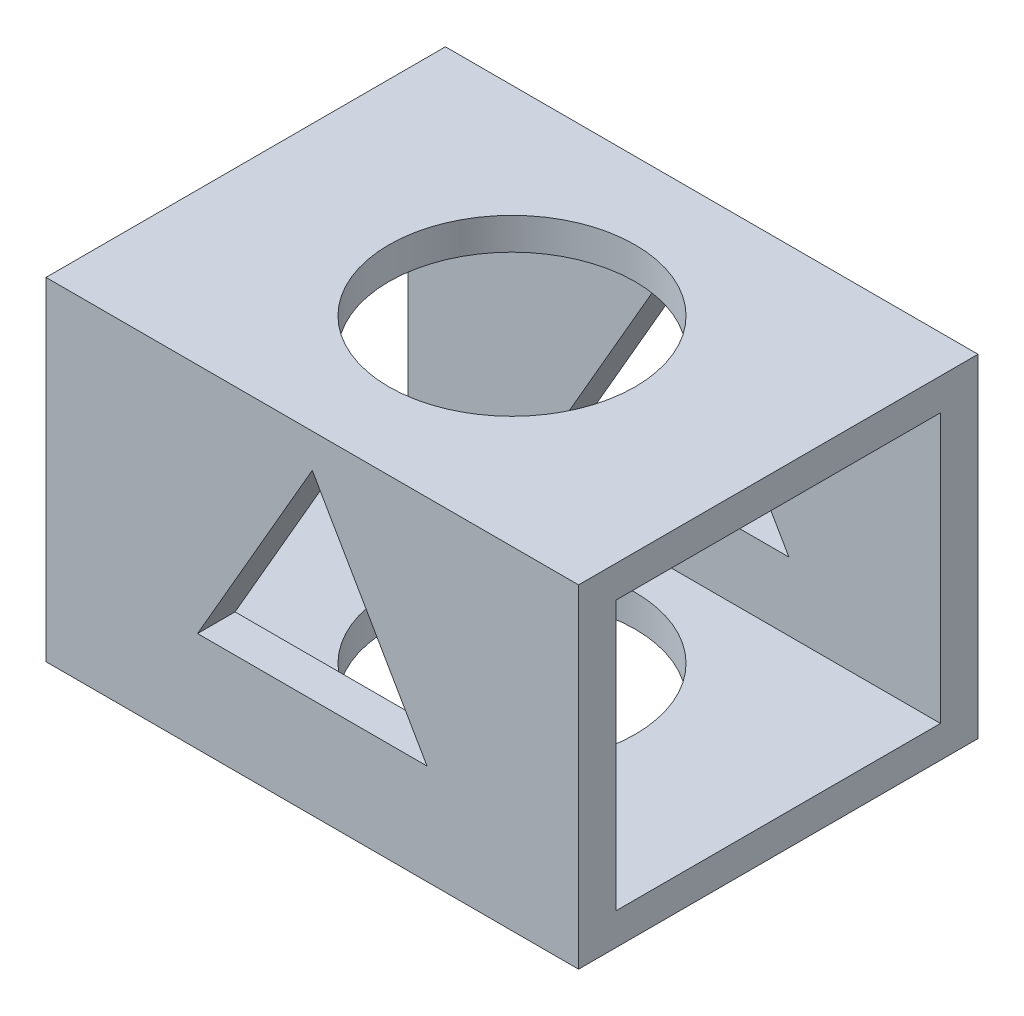
SolidWorks part; units mm, degrees
ref_plane "Front Plane" through (0, 0, 0) normal (0, 0, 1) x (1, 0, 0)
ref_plane "Top Plane" through (0, 0, 0) normal (0, 1, 0) x (1, 0, 0)
ref_plane "Right Plane" through (0, 0, 0) normal (1, 0, 0) x (0, 0, -1)
sketch "Sketch1" plane through (0, 0, 0) normal (0, 0, 1) x (1, 0, 0)
  line L1 (-101.6, -63.5) -> (101.6, -63.5)
  line L2 (-101.6, -63.5) -> (-101.6, 63.5)
  line L3 (-101.6, 63.5) -> (101.6, 63.5)
  line L4 (101.6, -63.5) -> (101.6, 63.5)
  line L5 (-101.6, -63.5) -> (101.6, 63.5) construction
  line L6 (-101.6, 63.5) -> (101.6, -63.5) construction
  point P0 (0, 0)
  dimension "D1" = 203.2
  dimension "D2" = 127
extrude "Boss-Extrude1" add sketch "Sketch1" along normal mid plane 152.4
sketch "Sketch2" plane through (0, 0, 76.2) normal (0, 0, 1) x (1, 0, 0)
  line L1 (0, 50.5506) -> (-43.7781, -25.2753)
  line L2 (-43.7781, -25.2753) -> (43.7781, -25.2753)
  line L3 (43.7781, -25.2753) -> (0, 50.5506)
  circle A0 centre (0, 0) radius 25.2753 construction
extrude "Cut-Extrude1" cut sketch "Sketch2" against normal through all
sketch "Sketch3" plane through (101.6, 0, 0) normal (1, 0, 0) x (0, 0, -1)
  line L1 (-61.8845, -51.332) -> (61.8845, -51.332)
  line L2 (-61.8845, -51.332) -> (-61.8845, 51.332)
  line L3 (-61.8845, 51.332) -> (61.8845, 51.332)
  line L4 (61.8845, -51.332) -> (61.8845, 51.332)
  line L5 (-61.8845, -51.332) -> (61.8845, 51.332) construction
  line L6 (-61.8845, 51.332) -> (61.8845, -51.332) construction
  point P0 (0, 0)
extrude "Cut-Extrude2" cut sketch "Sketch3" against normal through all
sketch "Sketch4" plane through (0, 63.5, 0) normal (0, 1, 0) x (1, 0, 0)
  circle A0 centre (0, 0) radius 46.9609
extrude "Cut-Extrude3" cut sketch "Sketch4" against normal through all
